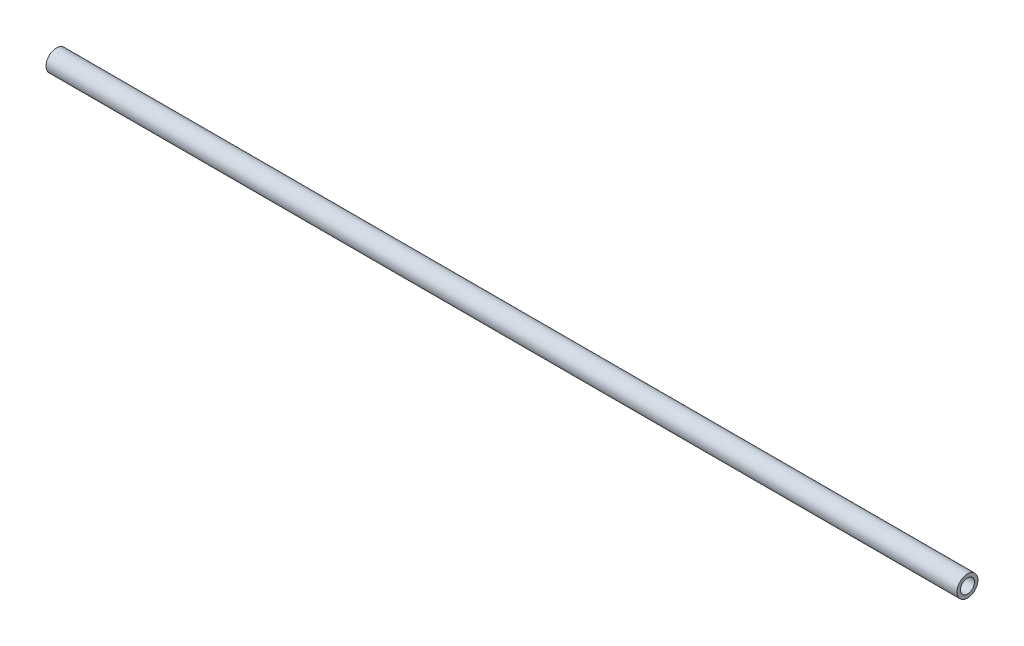
SolidWorks part; units mm, degrees
ref_plane "前视基准面" through (0, 0, 0) normal (0, 0, 1) x (1, 0, 0)
ref_plane "上视基准面" through (0, 0, 0) normal (0, 1, 0) x (1, 0, 0)
ref_plane "右视基准面" through (0, 0, 0) normal (1, 0, 0) x (0, 0, -1)
sketch "草图1" plane through (0, 0, 0) normal (1, 0, 0) x (0, 0, -1)
  circle A0 centre (0, 0) radius 1.5
  circle A1 centre (0, 0) radius 1
  dimension "D1" = 3
  dimension "D2" = 2
extrude "凸台-拉伸1" add sketch "草图1" along normal blind 130
